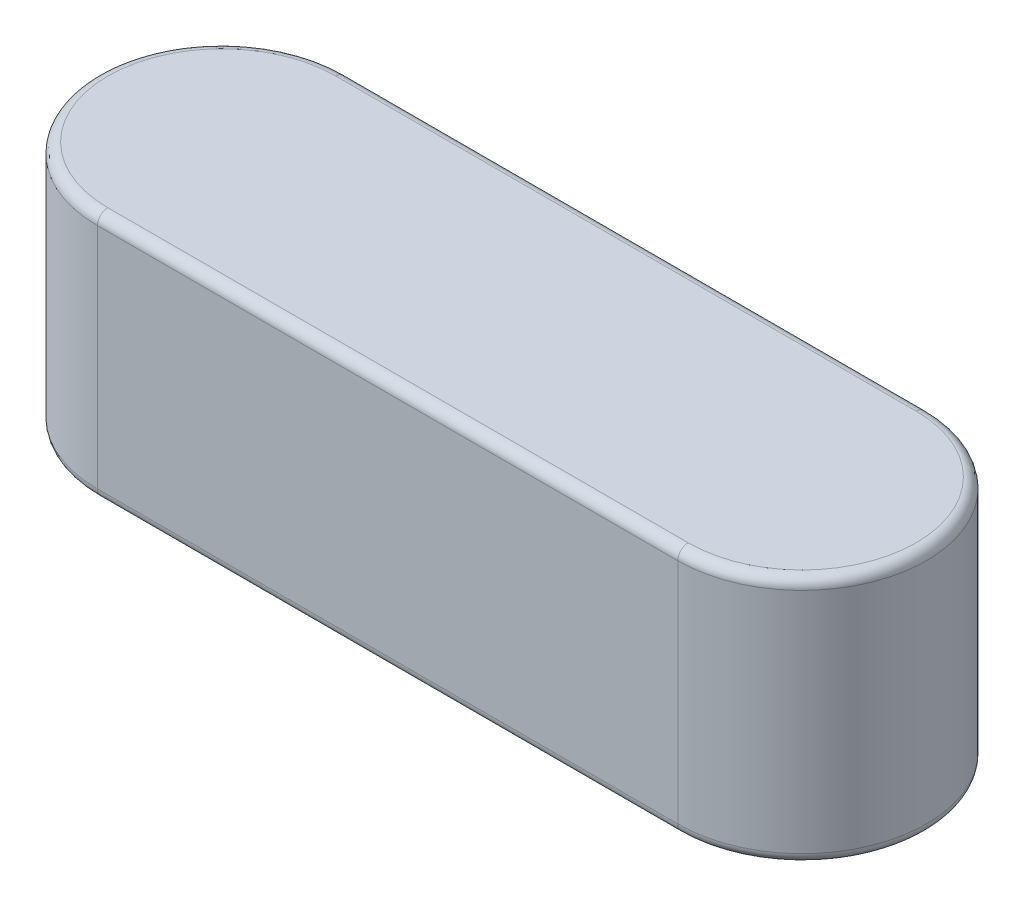
SolidWorks part; units mm, degrees
ref_plane "Front Plane" through (0, 0, 0) normal (0, 0, 1) x (1, 0, 0)
ref_plane "Top Plane" through (0, 0, 0) normal (0, 1, 0) x (1, 0, 0)
ref_plane "Right Plane" through (0, 0, 0) normal (1, 0, 0) x (0, 0, -1)
sketch "Sketch1" plane through (0, 0, 0) normal (0, 1, 0) x (1, 0, 0)
  line L1 (-14, 3) -> (0, 3)
  line L3 (-14, -3) -> (0, -3)
  arc A0 (0, -3) -> (0, 3) centre (0, 0) ccw
  arc A1 (-14, 3) -> (-14, -3) centre (-14, 0) ccw
  dimension "l" = 20
  dimension "b" = 6
extrude "Extrude1" add sketch "Sketch1" along normal blind 6
fillet "Fillet1" radius 0.25 8 edges at (-7, 0, -3) (3, 0, 0) (-17, 0, 0) (-7, 0, 3) (3, 6, 0) (-7, 6, 3) (-7, 6, -3) (-17, 6, 0)
